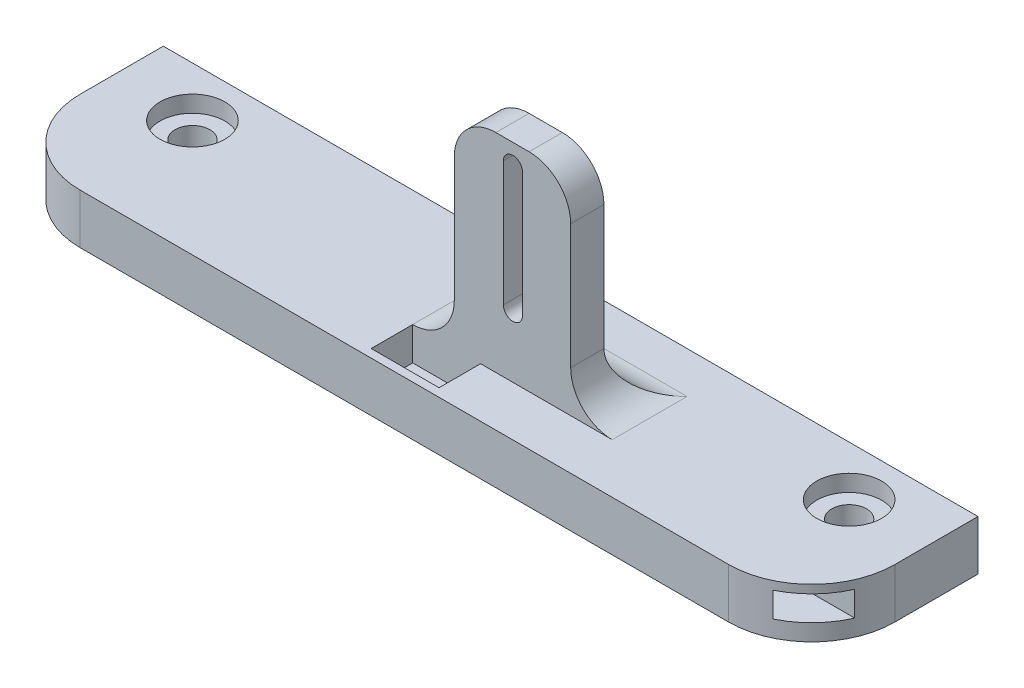
SolidWorks part; units mm, degrees
ref_plane "Alzado" through (0, 0, 0) normal (0, 0, 1) x (1, 0, 0)
ref_plane "Planta" through (0, 0, 0) normal (0, 1, 0) x (1, 0, 0)
ref_plane "Vista lateral" through (0, 0, 0) normal (1, 0, 0) x (0, 0, -1)
sketch "Croquis1" plane through (0, 0, 0) normal (0, 1, 0) x (1, 0, 0)
  line L1 (-39, -10) -> (39, -10)
  line L2 (-49, 0) -> (-49, 10)
  line L3 (-49, 10) -> (49, 10)
  line L4 (49, 0) -> (49, 10)
  line L5 (-49, -10) -> (49, 10) construction
  line L6 (-49, 10) -> (49, -10) construction
  line L7 (-49, 4) -> (-39.5, 4) construction
  line L8 (49, 4) -> (39.5, 4) construction
  circle A0 centre (-39.5, 4) radius 2.1
  circle A1 centre (39.5, 4) radius 2.1
  arc A2 (39, -10) -> (49, 0) centre (39, 0) ccw
  arc A3 (-39, -10) -> (-49, 0) centre (-39, 0) cw
  point P0 (0, 0)
  dimension "D1" = 10
extrude "Saliente-Extruir1" add sketch "Croquis1" along normal blind 6
sketch "Croquis2" plane through (0, 6, 0) normal (0, 1, 0) x (1, 0, 0)
  circle A0 centre (39.5, 4) radius 3.9
  circle A1 centre (-39.5, 4) radius 3.9
extrude "Cortar-Extruir1" cut sketch "Croquis2" against normal blind 2
sketch "Croquis3" plane through (0, 6, 0) normal (0, 1, 0) x (1, 0, 0)
  line L0 (0, 0) -> (0, 10) construction
  line L1 (49, 10) -> (-49, 10) construction
  line L2 (0, 10) -> (0, -10) construction
  line L3 (-39, -10) -> (39, -10) construction
  line L4 (0, 0) -> (14, 0) construction
  line L5 (14, -10) -> (14, -4) construction
  line L6 (14, -4) -> (0, -4)
  line L7 (0, -4) -> (0, 0)
  line L8 (0, 0) -> (14, 0)
  line L9 (14, 0) -> (14, -4)
extrude "Saliente-Extruir2" add sketch "Croquis3" along normal blind 25
fillet "Redondeo4" radius 5 3 edges at (7, 6, 0) (0, 6, 2) (14, 6, 2)
sketch "Croquis4" plane through (0, 0, 0) normal (0, 0, -1) x (-1, 0, 0)
  line L2 (-7.05, 28.5) -> (-7.05, 13.5) construction
  line L3 (-5.9, 28.5) -> (-5.9, 13.5)
  line L4 (-8.2, 28.5) -> (-8.2, 13.5)
  arc A0 (-5.9, 28.5) -> (-8.2, 28.5) centre (-7.05, 28.5) ccw
  arc A1 (-8.2, 13.5) -> (-5.9, 13.5) centre (-7.05, 13.5) ccw
  point P6 (-7.05, 21)
sketch "Croquis5" plane through (49, 0, 0) normal (1, 0, 0) x (0, 0, -1)
  line L0 (0, 6) -> (-6.5, 6) construction
  line L2 (-9, 10) -> (-4, 10)
  line L3 (-9, 10) -> (-9, 2)
  line L4 (-9, 2) -> (-4, 2)
  line L5 (-4, 10) -> (-4, 2)
  line L6 (-9, 10) -> (-4, 2) construction
  line L7 (-9, 2) -> (-4, 10) construction
extrude "Cortar-Extruir6" cut sketch "Croquis4" against normal blind 4
fillet "Redondeo7" radius 5 1 edges at (14, 31, 2)
fillet "Redondeo8" radius 5 1 edges at (0, 31, 2)
extrude "Cortar-Extruir9" cut sketch "Croquis5" against normal blind 54
sketch "Croquis11" plane through (0, 0, 4) normal (0, 0, 1) x (1, 0, 0)
  line L0 (48.1652, 6) -> (48.1652, 5.0034)
  line L1 (48.1652, 6) -> (48.1652, 2) construction
  line L2 (48.1652, 5.0034) -> (3.1652, 5.0034)
  line L3 (3.1652, 6) -> (48.1652, 6)
  line L4 (3.1652, 5.0034) -> (3.1652, 6)
extrude "Saliente-Extruir7" add sketch "Croquis11" along normal blind 5
sketch "Croquis12" plane through (0, 6, 0) normal (0, 1, 0) x (1, 0, 0)
  line L0 (49, 10) -> (49, 0) construction
  line L1 (14, -10) -> (39, -10) construction
  line L2 (49, 10) -> (57.1402, 10)
  line L3 (57.1402, 10) -> (57.7379, -14.0665)
  line L4 (57.7379, -14.0665) -> (14, -12.5612)
  line L5 (14, -12.5612) -> (14, -10)
  line L6 (14, -10) -> (39, -10)
  line L7 (49, 0) -> (49, 10)
  arc A0 (39, -10) -> (49, 0) centre (39, 0) ccw
  dimension "D1" = 10
extrude "Cortar-Extruir10" cut sketch "Croquis12" against normal blind 5
